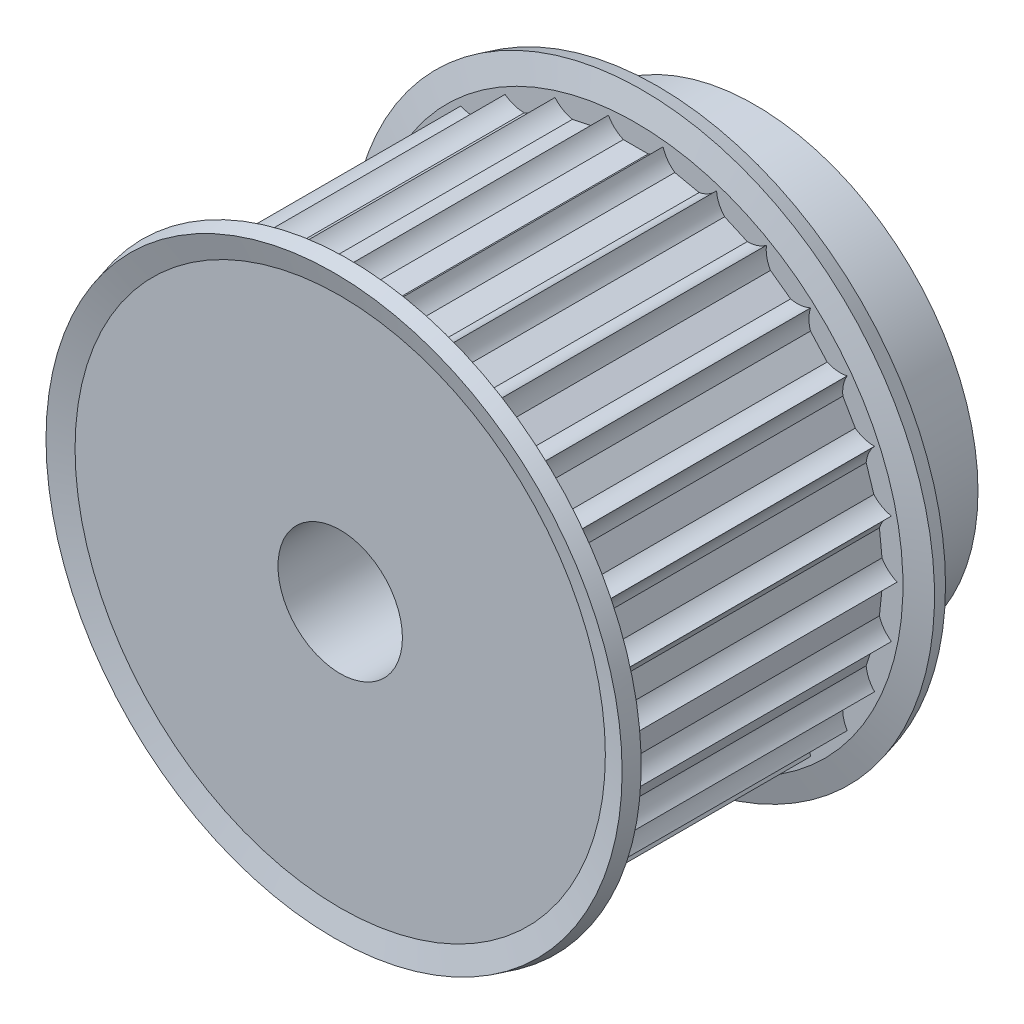
SolidWorks part; units mm, degrees
ref_plane "Front Plane" through (0, 0, 0) normal (0, 0, 1) x (1, 0, 0)
ref_plane "Top Plane" through (0, 0, 0) normal (0, 1, 0) x (1, 0, 0)
ref_plane "Right Plane" through (0, 0, 0) normal (1, 0, 0) x (0, 0, -1)
sketch "Sketch1" plane through (0, 0, 0) normal (1, 0, 0) x (0, 0, -1)
  line L0 (0, 6) -> (40, 6)
  line L1 (40, 6) -> (40, 21.5)
  line L2 (40, 21.5) -> (30, 21.5)
  line L3 (30, 21.5) -> (30, 27.25)
  line L4 (30, 27.25) -> (0, 27.25)
  line L5 (0, 27.25) -> (0, 6)
  line L6 (0, 0) -> (50000, 0) construction
  dimension "D1" = 30
  dimension "D2" = 21.25
  dimension "D3" = 10
  dimension "D4" = 6
  dimension "D5" = 15.5
revolve "Revolve1" add sketch "Sketch1" angle 360 about L6
sketch "Sketch2" plane through (0, 0, 0) normal (0, 0, 1) x (1, 0, 0)
  line L1 (3.75, 26.5) -> (3.6742, 26.5)
  line L2 (3.75, 26.5) -> (3.75, 28.5)
  line L3 (3.75, 28.5) -> (-3.75, 28.5)
  line L4 (-3.75, 26.5) -> (-3.75, 28.5)
  line L5 (-3.6742, 26.5) -> (-3.75, 26.5)
  line L6 (-1.199, 23.75) -> (1.199, 23.75)
  arc A0 (2.9394, 25.9) -> (1.199, 23.75) centre (0, 26.5) cw
  arc A1 (2.9394, 25.9) -> (3.6742, 26.5) centre (3.6742, 25.75) cw
  arc A2 (-2.9394, 25.9) -> (-3.6742, 26.5) centre (-3.6742, 25.75) ccw
  arc A3 (-1.199, 23.75) -> (-2.9394, 25.9) centre (0, 26.5) cw
  point P11 (3, 26.5)
  point P14 (-3, 26.5)
  dimension "D1" = 2
  dimension "D2" = 3
  dimension "D5" = 0.75
  dimension "D3" = 7.5
  dimension "D4" = 26.5
  dimension "D6" = 2.75
extrude "Cut-Extrude1" cut sketch "Sketch2" against normal blind 35
sketch "Sketch3" plane through (0, 0, 0) normal (0, 0, 1) x (1, 0, 0)
  point P0 (0, 0)
ref_axis "Axis1" through (0, 0, 0) along (0, 0, 1)
pattern_circular "CirPattern1" count 30 over 360 about axis through (0, 0, 0) along (0, 0, 1) of "Cut-Extrude1"
sketch "Sketch4" plane through (0, 0, 0) normal (1, 0, 0) x (0, 0, -1)
  line L3 (0, 25.7648) -> (1.5, 25.7648)
  line L8 (1.5, 25.7648) -> (0.0511, 25.3765)
  line L9 (1.5, 25.7648) -> (0.8569, 28.1648)
  line L10 (0.0511, 25.3765) -> (-0.592, 27.7765)
  line L11 (0.8569, 28.1648) -> (-0.592, 27.7765)
  line L12 (30, 25.0648) -> (0, 25.0648) construction
  line L14 (15, 25.0648) -> (15, -29.3474) construction
  line L15 (1.5, 25.7648) -> (0, 25.7648)
  line L16 (1.5, 25.7648) -> (1.5, 20.7648)
  line L17 (1.5, 20.7648) -> (0, 20.7648)
  line L18 (0, 25.7648) -> (0, 20.7648)
  line L19 (30, 25.0648) -> (30, 23.4803)
  line L20 (30, 25.7648) -> (30, 20.7648)
  line L21 (28.5, 20.7648) -> (30, 20.7648)
  line L22 (30, 25.0648) -> (0, 25.0648)
  line L23 (0, 25.0648) -> (0, 23.4803)
  line L24 (0, 23.4803) -> (30, 23.4803)
  line L25 (30, 23.4803) -> (30, 25.0648)
  line L26 (30, 25.0648) -> (0, 25.0648)
  line L27 (0, 25.0648) -> (0, 23.4803)
  line L28 (0, 23.4803) -> (30, 23.4803)
  line L29 (30, 23.4803) -> (30, 25.0648)
  line L30 (28.5, 25.7648) -> (28.5, 20.7648)
  line L31 (28.5, 25.7648) -> (30, 25.7648)
  line L32 (29.1431, 28.1648) -> (30.592, 27.7765)
  line L33 (29.9489, 25.3765) -> (30.592, 27.7765)
  line L34 (28.5, 25.7648) -> (29.1431, 28.1648)
  line L35 (28.5, 25.7648) -> (29.9489, 25.3765)
  line L36 (30, 25.7648) -> (28.5, 25.7648)
  dimension "D1" = 1.5
  dimension "D2" = 0.7
  dimension "D3" = 1.5
  dimension "D4" = 165
  dimension "D5" = 2.4
  dimension "D6" = 0
revolve "Revolve3" add sketch "Sketch4" angle 360 about axis through (0, 0, 0) along (0, 0, 1)
